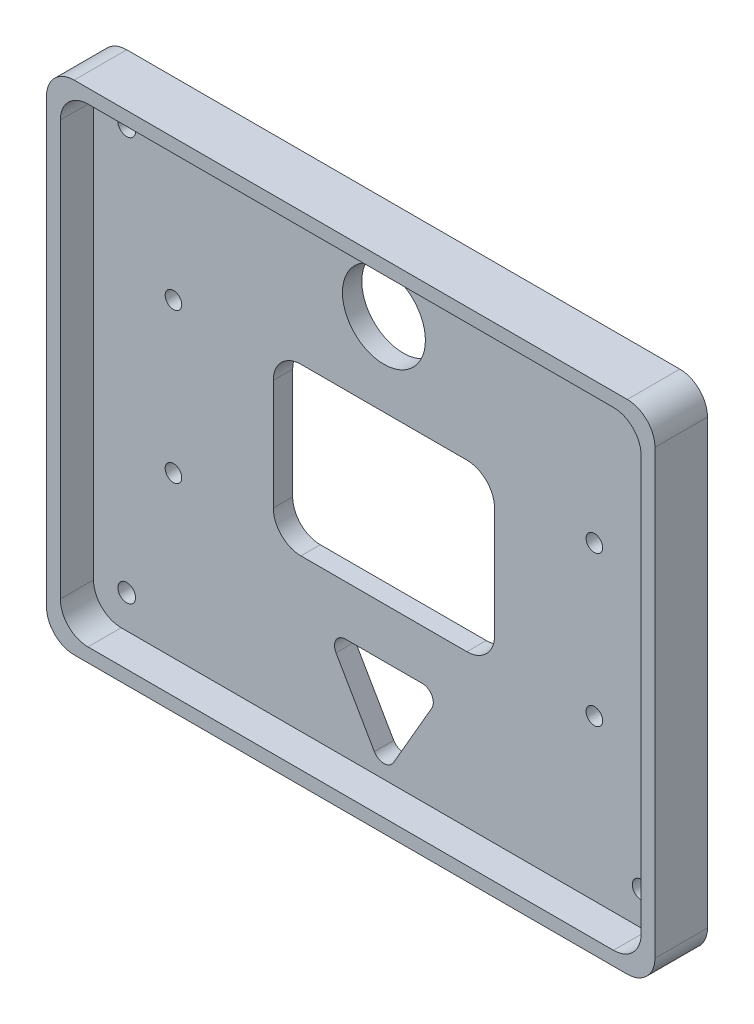
SolidWorks part; units mm, degrees
ref_plane "Front Plane" through (0, 0, 0) normal (0, 0, 1) x (1, 0, 0)
ref_plane "Top Plane" through (0, 0, 0) normal (0, 1, 0) x (1, 0, 0)
ref_plane "Right Plane" through (0, 0, 0) normal (1, 0, 0) x (0, 0, -1)
sketch "Sketch1" plane through (0, 0, 0) normal (0, 0, 1) x (1, 0, 0)
  line L0 (0, 0) -> (46.5, 0) construction
  line L1 (50, -45) -> (-50, -45)
  line L2 (55, -40) -> (55, 40)
  line L3 (50, 45) -> (-50, 45)
  line L4 (-55, -40) -> (-55, 40)
  line L5 (55, -45) -> (-55, 45) construction
  line L6 (55, 45) -> (-55, -45) construction
  line L7 (0, 0) -> (-46.5, 0) construction
  line L8 (-46.5, 0) -> (-46.5, 36.5) construction
  line L9 (46.5, 0) -> (46.5, 36.5) construction
  line L10 (0, 0) -> (0, 13.55) construction
  line L11 (0, 13.55) -> (38.05, 13.55) construction
  line L12 (38.05, 13.55) -> (38.05, -13.55) construction
  circle A0 centre (-46.5, 36.5) radius 1.6
  circle A1 centre (46.5, 36.5) radius 1.6
  circle A2 centre (46.5, -36.5) radius 1.6
  circle A3 centre (-46.5, -36.5) radius 1.6
  arc A4 (55, 40) -> (50, 45) centre (50, 40) ccw
  arc A5 (55, -40) -> (50, -45) centre (50, -40) cw
  arc A6 (-50, -45) -> (-55, -40) centre (-50, -40) cw
  arc A7 (-55, 40) -> (-50, 45) centre (-50, 40) cw
  circle A8 centre (38.05, 13.55) radius 1.5
  circle A9 centre (38.05, -13.55) radius 1.5
  circle A10 centre (-38.05, -13.55) radius 1.5
  circle A11 centre (-38.05, 13.55) radius 1.5
  point P0 (0, 0)
  dimension "D6" = 3.2
  dimension "D7" = 3.2
  dimension "D8" = 5
  dimension "D11" = 3
  dimension "D13" = 3
  dimension "D1" = 110
  dimension "D2" = 90
  dimension "D3" = 46.5
  dimension "D4" = 46.5
  dimension "D5" = 36.5
  dimension "D9" = 13.55
  dimension "D10" = 38.05
  dimension "D12" = 27.1
extrude "Boss-Extrude1" add sketch "Sketch1" along normal blind 3.5
ref_plane "Plane1" through (0, 0, 0) normal (0, 0, -1) x (-1, 0, 0)
sketch "Sketch2" plane through (0, 0, 0) normal (0, 0, -1) x (-1, 0, 0)
  line L0 (0, 0) -> (0, 30) construction
  line L1 (-15, -15) -> (15, -15)
  line L2 (-20, -10) -> (-20, 10)
  line L3 (-15, 15) -> (15, 15)
  line L4 (20, -10) -> (20, 10)
  line L5 (-20, -15) -> (20, 15) construction
  line L6 (-20, 15) -> (20, -15) construction
  line L7 (0, 0) -> (0, -30) construction
  line L9 (1.7321, -39) -> (8.6603, -27)
  line L10 (6.9282, -24) -> (-6.9282, -24)
  line L11 (-8.6603, -27) -> (-1.7321, -39)
  arc A0 (20, 10) -> (15, 15) centre (15, 10) ccw
  arc A1 (20, -10) -> (15, -15) centre (15, -10) cw
  arc A2 (-15, -15) -> (-20, -10) centre (-15, -10) cw
  arc A3 (-20, 10) -> (-15, 15) centre (-15, 10) cw
  circle A4 centre (0, 30) radius 7.5
  circle A5 centre (0, -30) radius 6 construction
  arc A6 (1.7321, -39) -> (-1.7321, -39) centre (0, -38) cw
  arc A7 (8.6603, -27) -> (6.9282, -24) centre (6.9282, -26) ccw
  arc A8 (-8.6603, -27) -> (-6.9282, -24) centre (-6.9282, -26) cw
  point P0 (0, 0)
  dimension "D3" = 5
  dimension "D5" = 15
  dimension "D7" = 12
  dimension "D8" = 2
  dimension "D1" = 40
  dimension "D2" = 30
  dimension "D4" = 30
  dimension "D6" = 30
extrude "Cut-Extrude1" cut sketch "Sketch2" against normal blind 10
ref_plane "Plane2" through (0, 0, 3.5) normal (0, 0, 1) x (1, 0, 0)
sketch "Sketch3" plane through (0, 0, 3.5) normal (0, 0, 1) x (1, 0, 0)
  line L1 (50, -45) -> (-50, -45)
  line L2 (55, -40) -> (55, 40)
  line L3 (50, 45) -> (-50, 45)
  line L4 (-55, -40) -> (-55, 40)
  line L5 (55, -45) -> (-55, 45) construction
  line L6 (55, 45) -> (-55, -45) construction
  arc A0 (55, 40) -> (50, 45) centre (50, 40) ccw
  arc A1 (50, -45) -> (55, -40) centre (50, -40) ccw
  arc A2 (-50, -45) -> (-55, -40) centre (-50, -40) cw
  arc A3 (-50, 45) -> (-55, 40) centre (-50, 40) ccw
  point P0 (0, 0)
  dimension "D1" = 5
extrude "Boss-Extrude2" add sketch "Sketch3" along normal blind 6
ref_plane "Plane3" through (0, 0, 9.5) normal (0, 0, 1) x (1, 0, 0)
sketch "Sketch4" plane through (0, 0, 9.5) normal (0, 0, 1) x (1, 0, 0)
  line L1 (47.5, -42.5) -> (-47.5, -42.5)
  line L2 (52.5, -37.5) -> (52.5, 37.5)
  line L3 (47.5, 42.5) -> (-47.5, 42.5)
  line L4 (-52.5, -37.5) -> (-52.5, 37.5)
  line L5 (52.5, -42.5) -> (-52.5, 42.5) construction
  line L6 (52.5, 42.5) -> (-52.5, -42.5) construction
  arc A0 (-47.5, -42.5) -> (-52.5, -37.5) centre (-47.5, -37.5) cw
  arc A1 (47.5, -42.5) -> (52.5, -37.5) centre (47.5, -37.5) ccw
  arc A2 (52.5, 37.5) -> (47.5, 42.5) centre (47.5, 37.5) ccw
  arc A3 (-52.5, 37.5) -> (-47.5, 42.5) centre (-47.5, 37.5) cw
  point P0 (0, 0)
  dimension "D3" = 5
  dimension "D1" = 105
  dimension "D2" = 85
extrude "Cut-Extrude2" cut sketch "Sketch4" against normal blind 6
